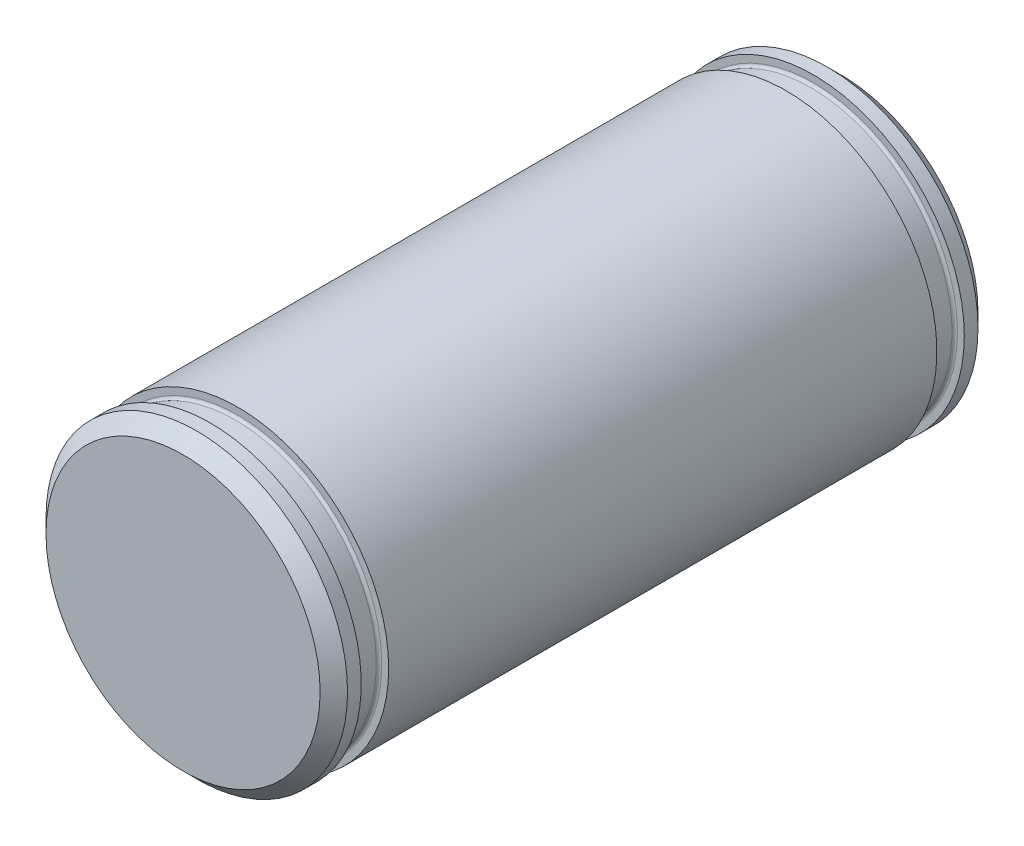
SolidWorks part; units mm, degrees
ref_plane "Plan de face" through (0, 0, 0) normal (0, 0, 1) x (1, 0, 0)
ref_plane "Plan de dessus" through (0, 0, 0) normal (0, 1, 0) x (1, 0, 0)
ref_plane "Plan de droite" through (0, 0, 0) normal (1, 0, 0) x (0, 0, -1)
sketch "Esquisse1" plane through (0, 0, 0) normal (0, 0, 1) x (1, 0, 0)
  circle A0 centre (0, 0) radius 5.5
  dimension "D1" = 11
extrude "Extrusion1" add sketch "Esquisse1" along normal mid plane 24
chamfer "Chanfrein1" distance 0.5 angle 45 1 edges at (5.5, 0, 12)
chamfer "Chanfrein2" distance 0.5 angle 45 1 edges at (5.5, 0, -12)
ref_plane "Plan1" through (0, 0, 24) normal (-1, 0, 0) x (0, 1, 0)
sketch "Esquisse3" plane through (0, 0, 24) normal (-1, 0, 0) x (0, 1, 0)
  line L0 (5.25, 13) -> (6.6, 13)
  line L1 (6.6, 13) -> (6.6, 14)
  line L2 (6.6, 14) -> (5.25, 14)
  line L3 (5.15, 13.9) -> (5.15, 13.1)
  line L4 (0, -50) -> (0, 50) construction
  arc A0 (5.15, 13.1) -> (5.25, 13) centre (5.25, 13.1) ccw
  arc A1 (5.15, 13.9) -> (5.25, 14) centre (5.25, 13.9) cw
  dimension "D1" = 0.1
  dimension "D2" = 0.1
  dimension "D3" = 10
revolve "Gorge pour ANSI B27.8M - 3DM1-11, Circlip haut rendement1" cut sketch "Esquisse3"
mirror "Symétrie1" about plane through (0, 0, 0) normal (0, 0, 1) of "Gorge pour ANSI B27.8M - 3DM1-11, Circlip haut rendement1"
